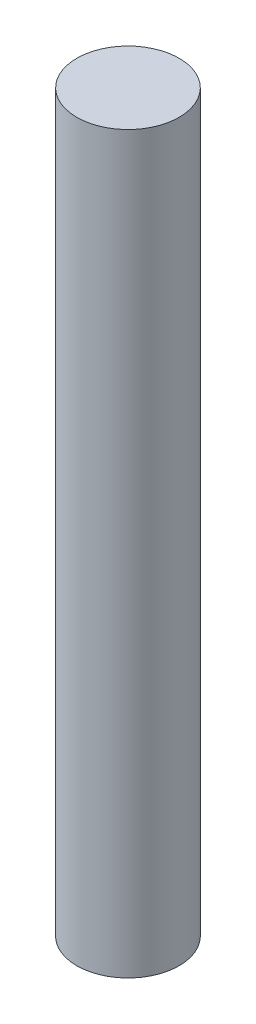
SolidWorks part; units mm, degrees
ref_plane "Front Plane" through (0, 0, 0) normal (0, 0, 1) x (1, 0, 0)
ref_plane "Top Plane" through (0, 0, 0) normal (0, 1, 0) x (1, 0, 0)
ref_plane "Right Plane" through (0, 0, 0) normal (1, 0, 0) x (0, 0, -1)
sketch "Sketch1" plane through (0, 0, 0) normal (0, 1, 0) x (1, 0, 0)
  circle A0 centre (0, 0) radius 1.95
extrude "Boss-Extrude1" add sketch "Sketch1" along normal blind 28
